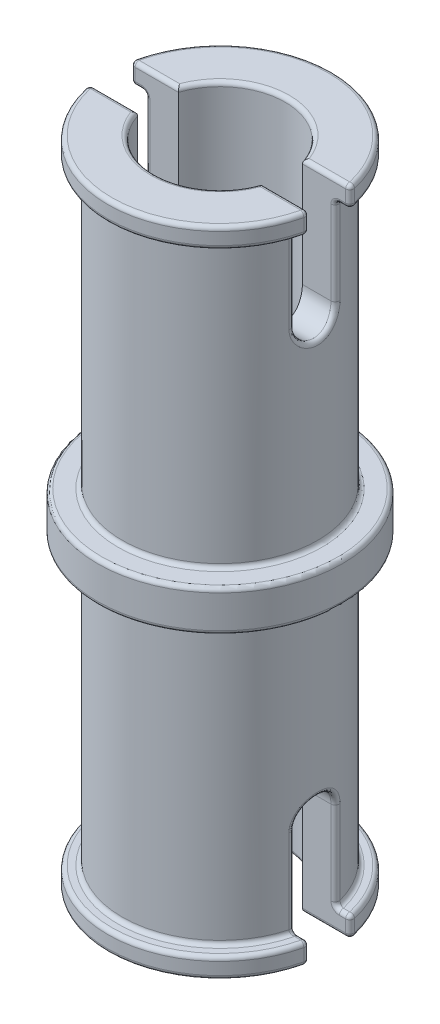
SolidWorks part; units mm, degrees
ref_plane "Front Plane" through (0, 0, 0) normal (0, 0, 1) x (1, 0, 0)
ref_plane "Top Plane" through (0, 0, 0) normal (0, 1, 0) x (1, 0, 0)
ref_plane "Right Plane" through (0, 0, 0) normal (1, 0, 0) x (0, 0, -1)
sketch "Sketch1" plane through (0, 0, 0) normal (1, 0, 0) x (0, 0, -1)
  line L0 (0, 0) -> (0, 13.1224) construction
  line L1 (2.4, 0.5) -> (2.4, 7.5)
  line L2 (2.4, 7.5) -> (3, 7.5)
  line L3 (3, 7.5) -> (3, 8.5)
  line L4 (2.4, 0.5) -> (2.75, 0.5)
  line L5 (2.75, 0.5) -> (2.75, 0)
  line L6 (2.75, 0) -> (1.6, 0)
  line L7 (3, 8.5) -> (2.4, 8.5)
  line L8 (2.4, 8.5) -> (2.4, 16)
  line L9 (2.4, 16) -> (0, 16)
  line L10 (0, 16) -> (0, 7.5)
  line L11 (1.6, 7.5) -> (1.6, 0)
  line L12 (1.6, 7.5) -> (0, 7.5)
  dimension "D1" = 7.5
  dimension "D2" = 2.4
  dimension "D3" = 3
  dimension "D4" = 1
  dimension "D5" = 0.5
  dimension "D6" = 2.75
  dimension "D7" = 0.8
  dimension "D8" = 7.5
revolve "Revolve1" add sketch "Sketch1" angle 360 about L0
sketch "Sketch2" plane through (0, 16, 0) normal (0, 1, 0) x (1, 0, 0)
  line L0 (0.9, -0.9) -> (2.2249, -0.9)
  line L1 (-0.9, -0.9) -> (-0.9, -2.2249)
  line L2 (-0.9, 2.2249) -> (-0.9, 0.9)
  line L3 (0.9, 2.2249) -> (0.9, 0.9)
  line L4 (-2.2249, -0.9) -> (-0.9, -0.9)
  line L5 (-2.2249, 0.9) -> (-0.9, 0.9)
  line L6 (0.9, -0.9) -> (0.9, -2.2249)
  line L9 (0.9, 0.9) -> (2.2249, 0.9)
  arc A0 (-0.9, 2.2249) -> (-2.2249, 0.9) centre (0, 0) ccw
  arc A1 (2.2249, 0.9) -> (0.9, 2.2249) centre (0, 0) ccw
  arc A2 (-2.2249, -0.9) -> (-0.9, -2.2249) centre (0, 0) ccw
  arc A3 (0.9, -2.2249) -> (2.2249, -0.9) centre (0, 0) ccw
  point P3 (0, 2.4)
  point P4 (0, -2.4)
  point P5 (-2.4, 0)
  point P6 (2.4, 0)
  point P7 (-0.9, 2.4)
  point P8 (-0.9, -2.4)
  point P9 (0.9, 2.4)
  point P10 (0.9, -2.4)
  point P13 (-2.4, 0.9)
  point P14 (2.4, 0.9)
extrude "Cut-Extrude1" cut sketch "Sketch2" against normal blind 7.5
sketch "Sketch3" plane through (0, 0, 0) normal (1, 0, 0) x (0, 0, -1)
  line L0 (0, 0) -> (0, 2.1578) construction
  line L1 (0.5, 2.6578) -> (0.5, 0)
  line L2 (-0.5, 2.6578) -> (-0.5, 0)
  line L3 (-0.5, 0) -> (0.5, 0)
  arc A0 (0.5, 2.6578) -> (-0.5, 2.6578) centre (0, 2.6578) ccw
extrude "Cut-Extrude2" cut sketch "Sketch3" against normal blind 10 and the other way blind 10
fillet "Fillet3" radius 0.8 12 edges at (-2.4, 16, 0) (-1.5624, 16, -0.9) (-0.9, 16, -1.5624) (0, 16, -2.4) (0.9, 16, -1.5624) (1.5624, 16, -0.9) (2.4, 16, 0) (1.5624, 16, 0.9) (0.9, 16, 1.5624) (0, 16, 2.4) (-0.9, 16, 1.5624) (-1.5624, 16, 0.9)
fillet "Fillet4" radius 0.1 65 edges at (0, 8.5, -3) (2.1371, 15.6334, 0.7725) (2.1371, 15.6334, -0.7725) (0.6657, 15.7657, 0.6657) (0.6657, 15.7657, -0.6657) (0.7725, 15.6334, 2.1371) (0.7725, 15.6334, -2.1371) (-0.7725, 15.6334, 2.1371) (-0.7725, 15.6334, -2.1371) (-0.6657, 15.7657, 0.6657) (-0.6657, 15.7657, -0.6657) (-2.1371, 15.6334, 0.7725) (-2.1371, 15.6334, -0.7725) (0, 7.5, -3) (2.4, 8.5, 0) (0.9, 11.85, -2.2249) (1.5624, 8.5, -0.9) (2.2249, 11.85, -0.9) (0.9, 8.5, -1.5624) (0.9, 11.85, -0.9) (0, 8.5, -2.4) (-2.2249, 11.85, -0.9) (-0.9, 8.5, -1.5624) (-0.9, 11.85, -2.2249) (-1.5624, 8.5, -0.9) (-0.9, 11.85, -0.9) (0, 8.5, 2.4) (2.2249, 11.85, 0.9) (0.9, 8.5, 1.5624) (0.9, 11.85, 2.2249) (1.5624, 8.5, 0.9) (0.9, 11.85, 0.9) (-2.4, 8.5, 0) (-0.9, 11.85, 2.2249) (-1.5624, 8.5, 0.9) (-2.2249, 11.85, 0.9) (-0.9, 8.5, 1.5624) (-0.9, 11.85, 0.9) (0, 0.5, 2.4) (0, 0.5, -2.4) (2.3473, 1.5789, -0.5) (2.3994, 3.155, -0.0527) (2.3473, 1.5789, 0.5) (-2.3473, 1.5789, -0.5) (-2.3994, 3.155, 0.0527) (-2.3473, 1.5789, 0.5) (0, 0.5, 2.75) (0, 0.5, -2.75) (0, 0, 2.75) (0, 0, -2.75) (0, 0, 1.6) (0, 0, -1.6) (2.112, 0, 0.5) (0, 7.5, -2.4) (2.7042, 0.25, 0.5) (2.5258, 0.5, 0.5) (-2.112, 0, -0.5) (-2.7042, 0.25, -0.5) (-2.5258, 0.5, -0.5) (-2.5258, 0.5, 0.5) (-2.7042, 0.25, 0.5) (-2.112, 0, 0.5) (2.112, 0, -0.5) (2.5258, 0.5, -0.5) (2.7042, 0.25, -0.5)
sketch "Sketch4" plane through (0, 8.5, 0) normal (0, 1, 0) x (1, 0, 0)
  circle A0 centre (0, 0) radius 12.6871
extrude "Cut-Extrude3" cut sketch "Sketch4" along normal blind 10
ref_plane "Plane1" through (0, 8, 0) normal (0, 1, 0) x (1, 0, 0)
mirror "Mirror5" about plane through (0, 8, 0) normal (0, 1, 0) of bodies 104
